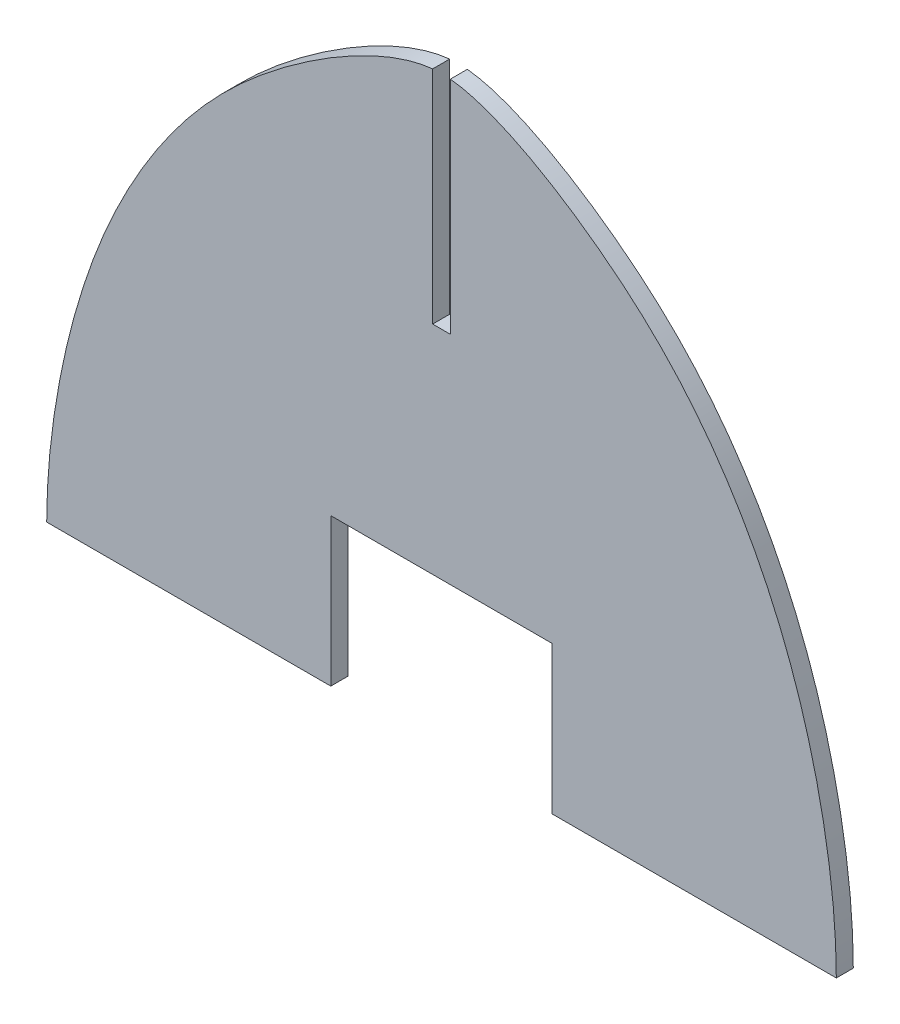
SolidWorks part; units mm, degrees
ref_plane "Front" through (0, 0, 0) normal (0, 0, 1) x (1, 0, 0)
ref_plane "Top" through (0, 0, 0) normal (0, 1, 0) x (1, 0, 0)
ref_plane "Right" through (0, 0, 0) normal (1, 0, 0) x (0, 0, -1)
sketch "Sketch2" plane through (0, 0, 0) normal (0, 0, 1) x (1, 0, 0)
  line L0 (0, 241.3) -> (53.7389, 241.3) construction
  line L1 (135.8472, 39.6875) -> (135.8472, 120.816) construction
  spline S0 degree 3 poles (0, 241.3) (14.7384, 241.3) (59.624, 216.3735) (96.7698, 175.9032) (127.184, 115.7381) (135.8472, 66.0913) (135.8472, 39.6875) knots 0 0 0 0 0.22773 0.472593 0.661218 1 1 1 1
sketch "Sketch3" plane through (0, 0, 0) normal (0, 0, 1) x (1, 0, 0)
  line L0 (0, 241.3) -> (0, 39.6875)
  line L1 (0, 39.6875) -> (135.8472, 39.6875)
  spline S0 degree 3 poles (3086.8812, -3680.7283) (-411.2791, 353.7794) (-18.9132, 301.94) (96.7698, 175.9032) (232.2786, -92.159) (-86.4504, -655.4051) (-1178.0632, 4844.4536) knots -1.398012 -1.398012 -1.398012 -1.398012 0.22773 0.472593 0.661218 3.668538 3.668538 3.668538 3.668538 only from (0, 241.3) to (135.8472, 39.6875) construction
  spline S1 degree 3 poles (0, 241.3) (14.7384, 241.3) (59.624, 216.3735) (96.7698, 175.9032) (127.184, 115.7381) (135.8472, 66.0913) (135.8472, 39.6875) knots 0 0 0 0 0.22773 0.472593 0.661218 1 1 1 1
extrude "Boss-Extrude1" add sketch "Sketch3" along normal blind 5.842
sketch "Sketch4" plane through (0, 0, 0) normal (0, 0, 1) x (1, 0, 0)
  line L1 (0, 39.6875) -> (38.1, 39.6875)
  line L2 (0, 39.6875) -> (0, 90.4875)
  line L3 (0, 90.4875) -> (38.1, 90.4875)
  line L4 (38.1, 39.6875) -> (38.1, 90.4875)
  line L5 (0, 241.3) -> (3.048, 241.3)
  line L6 (0, 241.3) -> (0, 165.1)
  line L7 (0, 165.1) -> (3.048, 165.1)
  line L8 (3.048, 241.3) -> (3.048, 165.1)
  dimension "D1" = 50.8
  dimension "D2" = 38.1
  dimension "D3" = 3.048
  dimension "D4" = 76.2
extrude "Cut-Extrude2" cut sketch "Sketch4" along normal through all
mirror "Mirror2" about plane through (0, 0, 0) normal (1, 0, 0) of bodies 103
